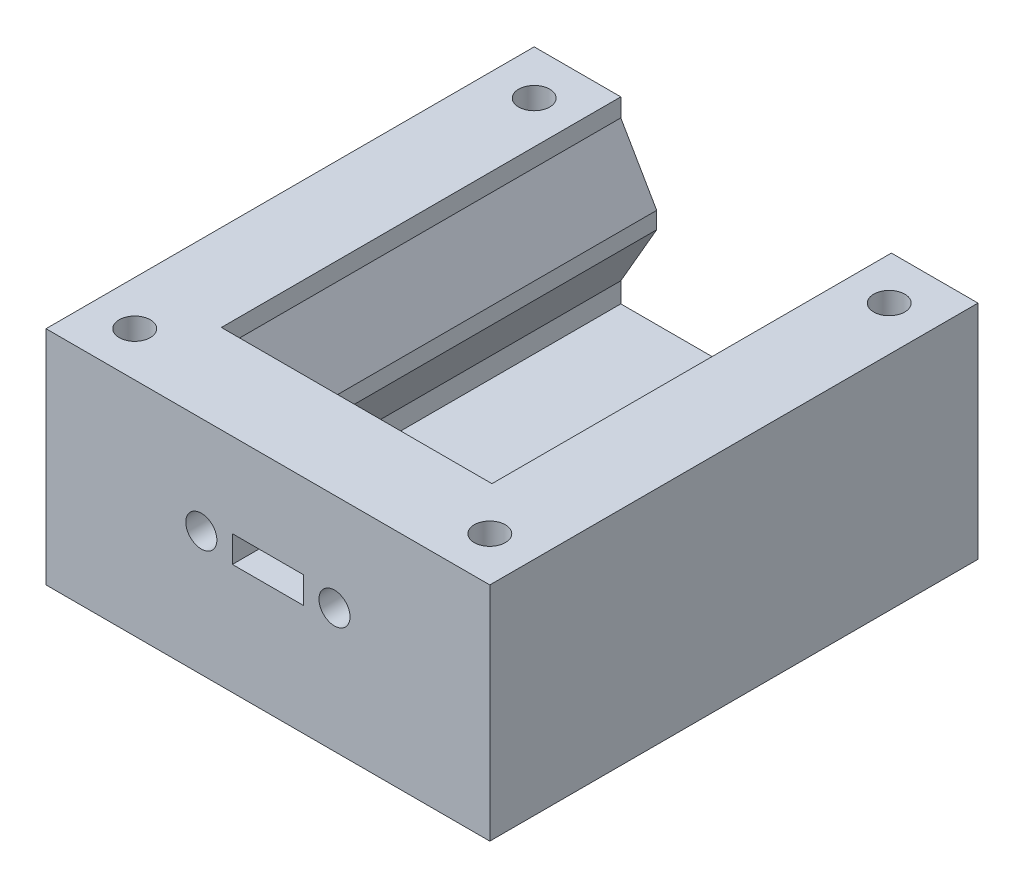
SolidWorks part; units mm, degrees
ref_plane "Piano frontale" through (0, 0, 0) normal (0, 0, 1) x (1, 0, 0)
ref_plane "Piano superiore" through (0, 0, 0) normal (0, 1, 0) x (1, 0, 0)
ref_plane "Piano destro" through (0, 0, 0) normal (1, 0, 0) x (0, 0, -1)
sketch "Schizzo1" plane through (0, 0, 0) normal (0, 0, 1) x (1, 0, 0)
  line L0 (-7.5, 1.5) -> (7.5, 1.5) construction
  line L1 (25, -12.5) -> (-25, -12.5)
  line L2 (25, -12.5) -> (25, 12.5)
  line L3 (25, 12.5) -> (-25, 12.5)
  line L4 (-25, -12.5) -> (-25, 12.5)
  line L5 (25, -12.5) -> (-25, 12.5) construction
  line L6 (25, 12.5) -> (-25, -12.5) construction
  line L8 (4, 0) -> (-4, 0)
  line L9 (4, 0) -> (4, 3)
  line L10 (4, 3) -> (-4, 3)
  line L11 (-4, 0) -> (-4, 3)
  line L12 (4, 0) -> (-4, 3) construction
  line L13 (4, 3) -> (-4, 0) construction
  circle A0 centre (-7.5, 1.5) radius 1.75
  circle A1 centre (7.5, 1.5) radius 1.75
  point P0 (0, 0)
  point P9 (0, 1.5)
  point P11 (0, 1.5)
  dimension "D1" = 3.5
  dimension "D2" = 15
  dimension "D3" = 11
  dimension "D4" = 25
  dimension "D5" = 50
  dimension "D6" = 8
  dimension "D7" = 3
extrude "Estrusione-Estrusione1" add sketch "Schizzo1" along normal blind 10
sketch "Schizzo2" plane through (0, 0, 0) normal (0, 0, -1) x (-1, 0, 0)
  line L0 (0, 12.5) -> (0, -12.5) construction
  line L1 (-15.0415, -7.5) -> (0, -7.5) construction
  line L2 (-15.2415, 12.5) -> (-25, 12.5)
  line L3 (-11, 3.5) -> (-11, 1.5) construction
  line L4 (-11, 1.5) -> (-15.0415, -5.5) construction
  line L5 (-15.0415, -5.5) -> (-15.0415, -7.5) construction
  line L6 (-25, 12.5) -> (25, 12.5) construction
  line L7 (25, -12.5) -> (-25, -12.5) construction
  line L8 (-11, 3.5) -> (-15.0415, 10.5) construction
  line L9 (-15.0415, 10.5) -> (-15.0415, 12.5) construction
  line L10 (-15.2415, 10.4464) -> (-15.2415, 12.7) construction
  line L11 (-15.2415, 10.4464) -> (-15.2415, 12.5)
  line L12 (-11.2, 3.4464) -> (-15.2415, 10.4464)
  line L13 (-11.2, 3.4464) -> (-11.2, 1.5536)
  line L14 (-11.2, 1.5536) -> (-15.2415, -5.4464)
  line L15 (-15.2415, -5.4464) -> (-15.2415, -7.7)
  line L16 (-15.2415, -7.7) -> (0, -7.7)
  line L17 (-15.2415, 12.7) -> (0, 12.7) construction
  line L18 (-15.0415, 12.5) -> (0, 12.5) construction
  line L19 (15.2415, 10.4464) -> (15.2415, 12.5)
  line L20 (11.2, 3.4464) -> (15.2415, 10.4464)
  line L21 (11.2, 3.4464) -> (11.2, 1.5536)
  line L22 (11.2, 1.5536) -> (15.2415, -5.4464)
  line L23 (15.2415, -5.4464) -> (15.2415, -7.7)
  line L24 (15.2415, -7.7) -> (0, -7.7)
  line L25 (-25, 12.5) -> (-25, -12.5)
  line L26 (-25, -12.5) -> (25, -12.5)
  line L27 (25, -12.5) -> (25, 12.5)
  line L28 (25, 12.5) -> (15.2415, 12.5)
  dimension "D1" = 150
  dimension "D2" = 150
  dimension "D3" = 2
  dimension "D4" = 2
  dimension "D5" = 2
  dimension "D6" = 11
  dimension "D7" = 20
  dimension "D8" = 0.2
extrude "Estrusione-Estrusione2" add sketch "Schizzo2" along normal blind 45 contours L14 L15 L16 L24 L23 L22 L21 L20 L19 L28 L27 L26 L25 L2 L11 L12 L13
sketch "Schizzo3" plane through (0, 0, 0) normal (0, 0, -1) x (-1, 0, 0)
  line L1 (-7.5, 4.75) -> (-10.3146, 3.125)
  line L2 (-10.3146, 3.125) -> (-10.3146, -0.125)
  line L3 (-10.3146, -0.125) -> (-7.5, -1.75)
  line L4 (-7.5, -1.75) -> (-4.6854, -0.125)
  line L5 (-4.6854, -0.125) -> (-4.6854, 3.125)
  line L6 (-4.6854, 3.125) -> (-7.5, 4.75)
  line L7 (7.5, 4.75) -> (4.6854, 3.125)
  line L8 (4.6854, 3.125) -> (4.6854, -0.125)
  line L9 (4.6854, -0.125) -> (7.5, -1.75)
  line L10 (7.5, -1.75) -> (10.3146, -0.125)
  line L11 (10.3146, -0.125) -> (10.3146, 3.125)
  line L12 (10.3146, 3.125) -> (7.5, 4.75)
  circle A0 centre (-7.5, 1.5) radius 1.75 construction
  circle A1 centre (7.5, 1.5) radius 1.75 construction
  circle A2 centre (-7.5, 1.5) radius 1.75 construction
  circle A3 centre (7.5, 1.5) radius 1.75 construction
  circle A4 centre (-7.5, 1.5) radius 2.8146 construction
  circle A5 centre (7.5, 1.5) radius 2.8146 construction
  dimension "D1" = 6.5
extrude "Taglio-Estrusione1" cut sketch "Schizzo3" against normal blind 3
sketch "Schizzo4" plane through (0, 12.5, 0) normal (0, 1, 0) x (1, 0, 0)
  line L0 (0, -5) -> (0, 40) construction
  line L1 (-20, -5) -> (20, -5) construction
  line L2 (-20, -5) -> (-20, 40) construction
  line L3 (-20, 40) -> (20, 40) construction
  line L4 (20, -5) -> (20, 40) construction
  line L5 (-25, -10) -> (-25, 45) construction
  line L6 (15.2415, 0) -> (-15.2415, 0) construction
  line L7 (25, -10) -> (-25, -10) construction
  line L8 (15.2415, 45) -> (25, 45) construction
  circle A0 centre (-20, -5) radius 1.75
  circle A1 centre (-20, 40) radius 1.75
  circle A2 centre (20, 40) radius 1.75
  circle A3 centre (20, -5) radius 1.75
  point P8 (0, 0)
  dimension "D1" = 3.5
  dimension "D2" = 5
  dimension "D3" = 5
  dimension "D4" = 5
extrude "Taglio-Estrusione2" cut sketch "Schizzo4" against normal through all
